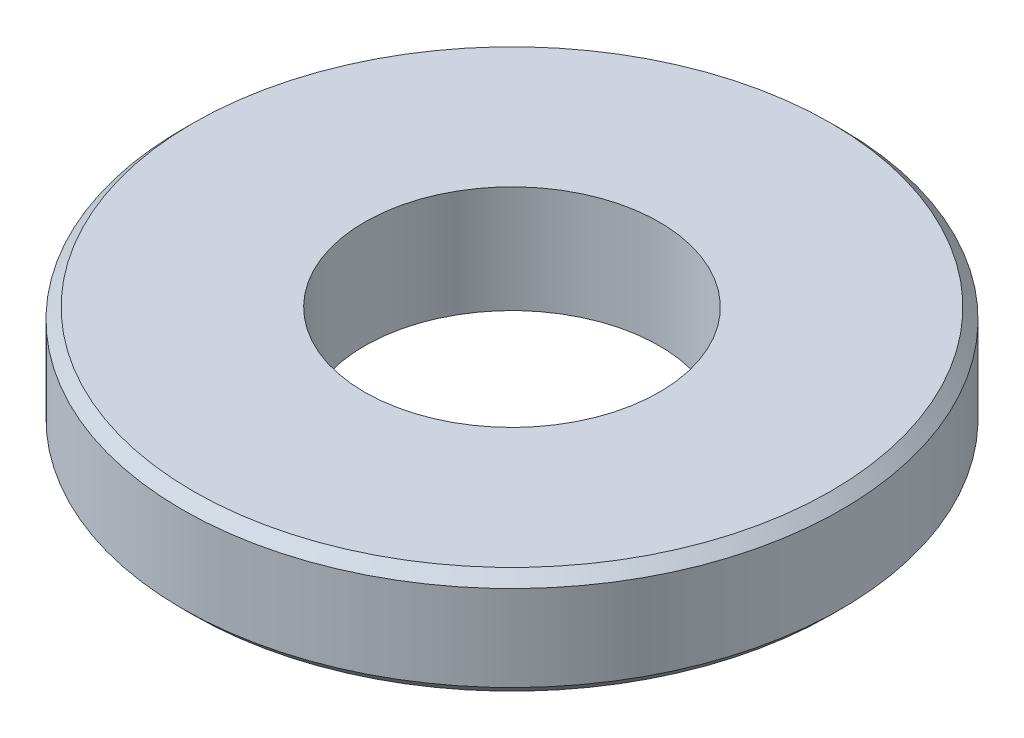
SolidWorks part; units mm, degrees
ref_plane "Front Plane" through (0, 0, 0) normal (0, 0, 1) x (1, 0, 0)
ref_plane "Top Plane" through (0, 0, 0) normal (0, 1, 0) x (1, 0, 0)
ref_plane "Right Plane" through (0, 0, 0) normal (1, 0, 0) x (0, 0, -1)
sketch "Sketch1" plane through (0, 0, 0) normal (0, 1, 0) x (1, 0, 0)
  circle A0 centre (0, 0) radius 5.5
  circle A1 centre (0, 0) radius 12.3
  dimension "D1" = 11
  dimension "D2" = 24.6
extrude "Boss-Extrude1" add sketch "Sketch1" along normal blind 4
chamfer "Chamfer1" distance 0.4 angle 45 2 edges at (0, 0, 12.3) (0, 4, 12.3)
